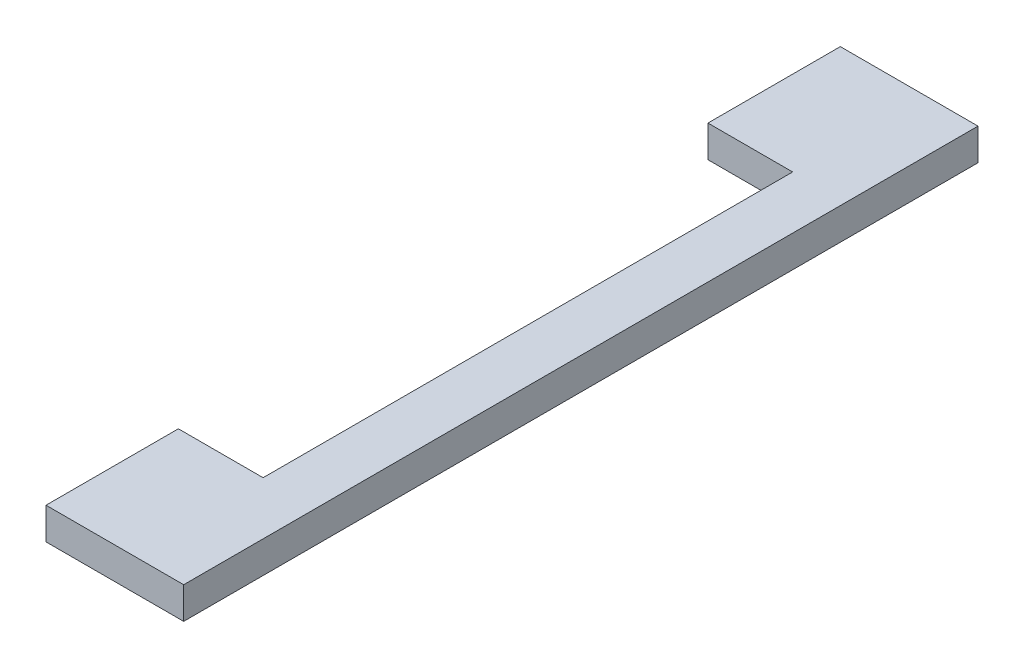
SolidWorks part; units mm, degrees
ref_plane "Front Plane" through (0, 0, 0) normal (0, 0, 1) x (1, 0, 0)
ref_plane "Top Plane" through (0, 0, 0) normal (0, 1, 0) x (1, 0, 0)
ref_plane "Right Plane" through (0, 0, 0) normal (1, 0, 0) x (0, 0, -1)
sketch "Sketch1" plane through (0, 0, 0) normal (0, 1, 0) x (1, 0, 0)
  line L0 (-17.4, -19.74) -> (-17.4, -44.74)
  line L1 (-17.4, 105.26) -> (8.6, 105.26)
  line L2 (-17.4, 105.26) -> (-17.4, 80.26)
  line L3 (-17.4, -44.74) -> (8.6, -44.74)
  line L4 (8.6, 105.26) -> (8.6, -44.74)
  line L5 (-17.4, 80.26) -> (-1.4, 80.26)
  line L7 (-17.4, -19.74) -> (-1.4, -19.74)
  line L8 (-1.4, 80.26) -> (-1.4, -19.74)
  dimension "D1" = 25
  dimension "D3" = 10
  dimension "D4" = 16
  dimension "D5" = 100
extrude "Boss-Extrude1" add sketch "Sketch1" along normal blind 6
